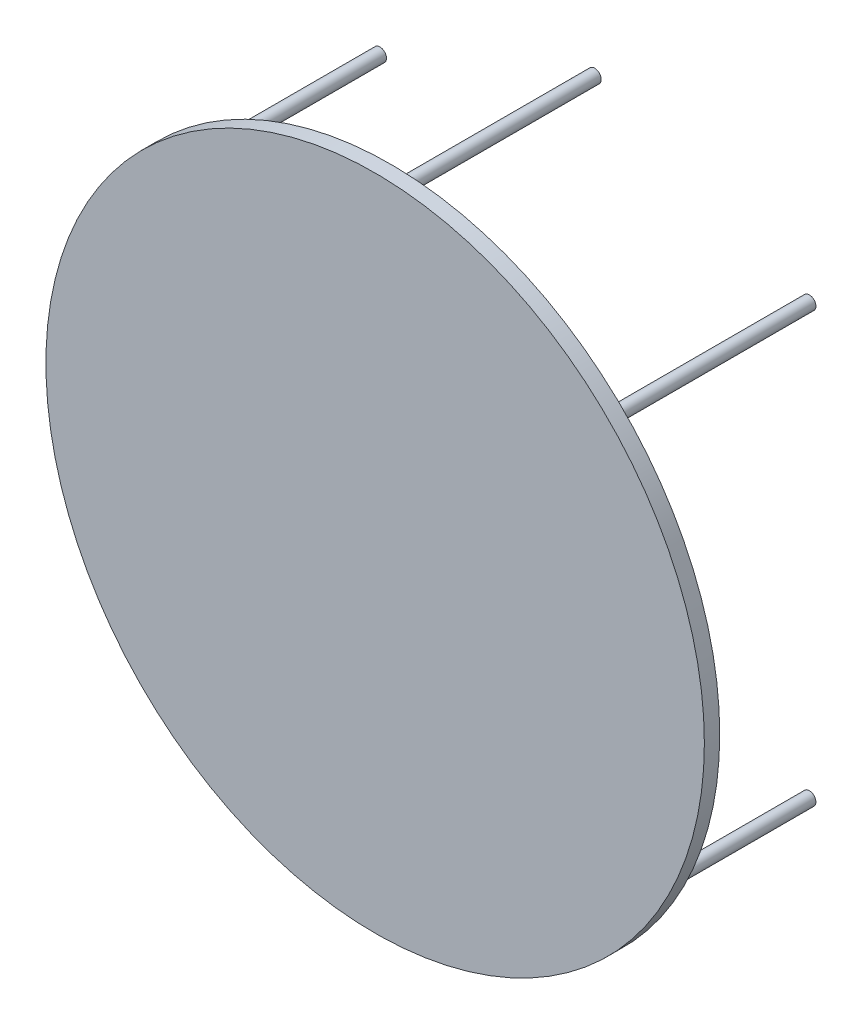
SolidWorks part; units mm, degrees
ref_plane "Front Plane" through (0, 0, 0) normal (0, 0, 1) x (1, 0, 0)
ref_plane "Top Plane" through (0, 0, 0) normal (0, 1, 0) x (1, 0, 0)
ref_plane "Right Plane" through (0, 0, 0) normal (1, 0, 0) x (0, 0, -1)
sketch "Sketch1" plane through (0, 0, 0) normal (0, 0, 1) x (1, 0, 0)
  circle A0 centre (0, 0) radius 114.3
  dimension "D1" = 228.6
extrude "Platform" add sketch "Sketch1" along normal blind 5.334
sketch "Sketch3" plane through (0, 0, 0) normal (0, 0, -1) x (-1, 0, 0)
  line L0 (0, 105.41) -> (0, -105.41) construction
  line L1 (0, -105.41) -> (105.41, 0) construction
  line L2 (105.41, 0) -> (0, 105.41) construction
  line L3 (0, 105.41) -> (-105.41, 0) construction
  line L4 (-105.41, 0) -> (0, -105.41) construction
  line L5 (-52.705, -52.705) -> (-74.5361, -74.5361) construction
  line L6 (-52.705, 52.705) -> (-74.5361, 74.5361) construction
  line L7 (52.705, 52.705) -> (74.5361, 74.5361) construction
  line L8 (52.705, -52.705) -> (74.5361, -74.5361) construction
  circle A1 centre (0, 105.41) radius 2.286
  circle A2 centre (-74.5361, 74.5361) radius 2.286
  circle A4 centre (-74.5361, -74.5361) radius 2.286
  circle A5 centre (0, -105.41) radius 2.286
  circle A6 centre (74.5361, -74.5361) radius 2.286
  circle A8 centre (74.5361, 74.5361) radius 2.286
  dimension "D2" = 4.572
  dimension "D3" = 4.572
  dimension "D5" = 4.572
  dimension "D6" = 4.572
  dimension "D7" = 4.572
  dimension "D9" = 4.572
extrude "Pegs" add sketch "Sketch3" along normal blind 70.866
